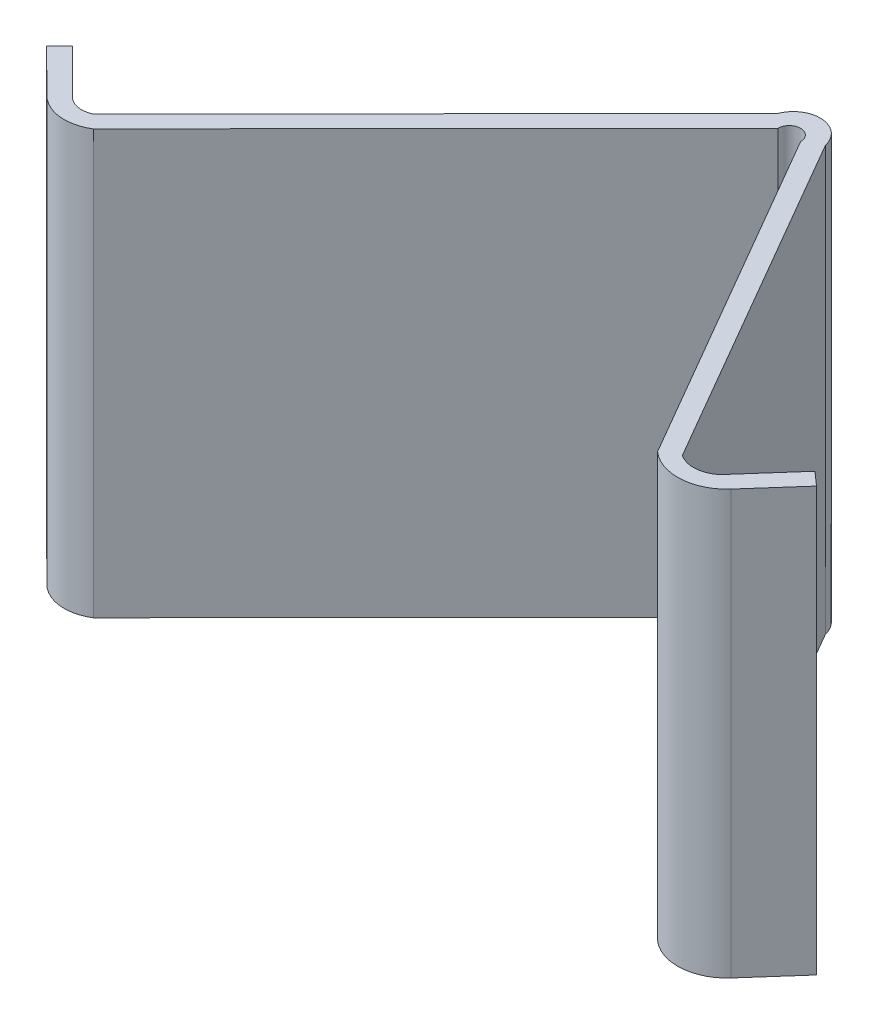
SolidWorks part; units mm, degrees
ref_plane "前基準面" through (0, 0, 0) normal (0, 0, 1) x (1, 0, 0)
ref_plane "上基準面" through (0, 0, 0) normal (0, 1, 0) x (1, 0, 0)
ref_plane "右基準面" through (0, 0, 0) normal (1, 0, 0) x (0, 0, -1)
sketch "草圖1" plane through (0, 0, 0) normal (0, 1, 0) x (1, 0, 0)
  line L0 (-45.4878, -38.6148) -> (10.9966, 18.0377)
  line L1 (-45.4878, -38.6148) -> (-43.3634, -40.733)
  line L2 (10.9966, 18.0377) -> (13.1211, 15.9196)
  line L3 (-43.3634, -40.733) -> (13.1211, 15.9196)
  line L4 (16.8986, 15.9196) -> (49.4822, -40.3237)
  line L5 (16.8986, 15.9196) -> (19.4945, 17.4234)
  line L6 (49.4822, -40.3237) -> (52.0781, -38.8199)
  line L7 (19.4945, 17.4234) -> (52.0781, -38.8199)
  line L8 (13.1211, 15.9196) -> (16.8986, 15.9196)
  line L9 (-52.0067, -39.7967) -> (-49.8886, -37.6722)
  line L10 (-52.0067, -39.7967) -> (-59.0883, -32.7361)
  line L11 (-49.8886, -37.6722) -> (-56.9701, -30.6117)
  line L12 (-59.0883, -32.7361) -> (-56.9701, -30.6117)
  line L17 (58.669, -37.6044) -> (65.2956, -30.1152)
  line L18 (58.669, -37.6044) -> (60.9158, -39.5924)
  line L19 (65.2956, -30.1152) -> (67.5423, -32.1032)
  line L20 (60.9158, -39.5924) -> (67.5423, -32.1032)
  arc A0 (18.3722, 13.3761) -> (11.3477, 14.141) centre (15.1528, 16.4481) ccw
  arc A1 (16.8986, 15.9196) -> (13.1211, 15.9196) centre (15.0098, 15.9196) ccw
  arc A2 (-43.3634, -40.733) -> (-52.0067, -39.7967) centre (-47.1014, -34.8768) cw
  arc A3 (-49.8886, -37.6722) -> (-45.4878, -38.6148) centre (-47.0796, -35.3018) ccw
  arc A4 (52.0781, -38.8199) -> (58.669, -37.6044) centre (54.7421, -34.788) ccw
  arc A5 (49.4822, -40.3237) -> (60.9158, -39.5924) centre (54.8313, -34.2087) ccw
  dimension "D1" = 3
  dimension "D2" = 3
  dimension "D3" = 3
  dimension "D4" = 10
  dimension "D5" = 75
  dimension "D6" = 80
  dimension "D7" = 65
  dimension "D8" = 90
  dimension "D9" = 10
  dimension "D10" = 3
extrude "填料-伸長1" add sketch "草圖1" along normal blind 70
